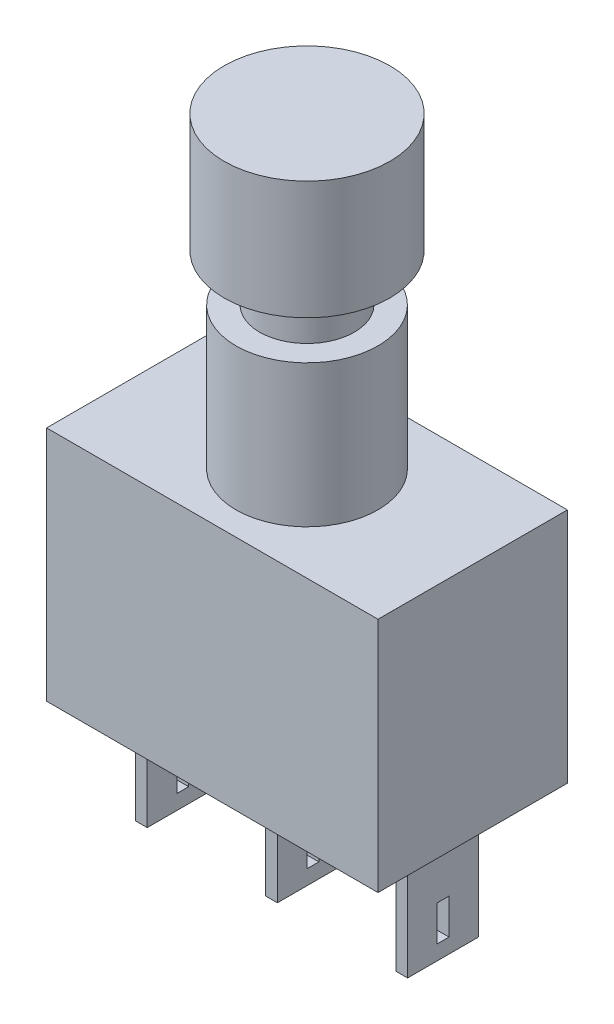
SolidWorks part; units mm, degrees
ref_plane "Front" through (0, 0, 0) normal (0, 0, 1) x (1, 0, 0)
ref_plane "Top" through (0, 0, 0) normal (0, 1, 0) x (1, 0, 0)
ref_plane "Right" through (0, 0, 0) normal (1, 0, 0) x (0, 0, -1)
sketch "Sketch2" plane through (0, 0, 0) normal (0, 1, 0) x (1, 0, 0)
  line L1 (-7, 4) -> (7, 4)
  line L2 (-7, 4) -> (-7, -4)
  line L3 (-7, -4) -> (7, -4)
  line L4 (7, 4) -> (7, -4)
  dimension "D1" = 14
  dimension "D2" = 8
  dimension "D3" = 4
  dimension "D4" = 7
extrude "Extrude1" add sketch "Sketch2" along normal blind 10
sketch "Sketch3" plane through (0, 10, 0) normal (0, 1, 0) x (-1, 0, 0)
  circle A0 centre (0, 0) radius 3
  dimension "D1" = 6
extrude "Extrude2" add sketch "Sketch3" along normal blind 6
sketch "Sketch4" plane through (0, 16, 0) normal (0, 1, 0) x (-1, 0, 0)
  circle A0 centre (0, 0) radius 2
  dimension "D1" = 4
extrude "Extrude3" add sketch "Sketch4" along normal blind 2
sketch "Sketch5" plane through (0, 18, 0) normal (0, 1, 0) x (-1, 0, 0)
  circle A0 centre (0, 0) radius 3.5
  dimension "D1" = 7
extrude "Extrude4" add sketch "Sketch5" along normal blind 5
sketch "Sketch6" plane through (0, 0, 0) normal (0, -1, 0) x (1, 0, 0)
  line L1 (0.25, 1.5) -> (-0.25, 1.5)
  line L2 (0.25, 1.5) -> (0.25, -1.5)
  line L3 (0.25, -1.5) -> (-0.25, -1.5)
  line L4 (-0.25, 1.5) -> (-0.25, -1.5)
  dimension "D1" = 3
  dimension "D2" = 0.5
  dimension "D3" = 1.5
  dimension "D4" = 0.25
extrude "Extrude5" add sketch "Sketch6" along normal blind 5
sketch "Sketch7" plane through (0, 0, 0) normal (0, -1, 0) x (1, 0, 0)
  line L0 (0.25, -1.5) -> (0.25, 1.5) construction
  line L1 (5.75, 1.5) -> (5.25, 1.5)
  line L2 (5.75, 1.5) -> (5.75, -1.5)
  line L3 (5.75, -1.5) -> (5.25, -1.5)
  line L4 (5.25, 1.5) -> (5.25, -1.5)
  line L7 (-7, 4) -> (7, 4) construction
  dimension "D1" = 3
  dimension "D2" = 0.5
  dimension "D3" = 5
  dimension "D4" = 2.5
extrude "Extrude6" add sketch "Sketch7" along normal blind 5
sketch "Sketch8" plane through (0, 0, 0) normal (0, -1, 0) x (1, 0, 0)
  line L0 (-0.25, 1.5) -> (-0.25, -1.5) construction
  line L1 (-5.25, 1.5) -> (-5.75, 1.5)
  line L2 (-5.25, 1.5) -> (-5.25, -1.5)
  line L3 (-5.25, -1.5) -> (-5.75, -1.5)
  line L4 (-5.75, 1.5) -> (-5.75, -1.5)
  line L5 (-7, 4) -> (7, 4) construction
  dimension "D1" = 3
  dimension "D2" = 0.5
  dimension "D3" = 5
  dimension "D4" = 2.5
extrude "Extrude7" add sketch "Sketch8" along normal blind 5
sketch "Sketch9" plane through (-5.75, 0, 0) normal (-1, 0, 0) x (0, 0, 1)
  line L0 (-1.5, -5) -> (-1.5, 0) construction
  line L1 (-0.25, -2.8767) -> (0.25, -2.8767)
  line L2 (-0.25, -2.8767) -> (-0.25, -4.3767)
  line L3 (-0.25, -4.3767) -> (0.25, -4.3767)
  line L4 (0.25, -2.8767) -> (0.25, -4.3767)
  dimension "D1" = 1.5
  dimension "D2" = 0.5
  dimension "D3" = 1.25
extrude "Cut-Extrude1" cut sketch "Sketch9" against normal through all
sketch "Sketch10" plane through (-7, 0, 0) normal (-1, 0, 0) x (0, 0, 1)
  line L0 (0, 29.892) -> (0, -5.892) construction
  line L1 (-8.5556, 23) -> (9.3025, 23) construction
  line L3 (-11.8469, 0) -> (13.8087, 0) construction
  line L4 (-4, 0) -> (4, 0) construction
  line L5 (-9.56, 18) -> (13.8087, 18) construction
  line L6 (-3.5, 18) -> (3.5, 18) construction
  line L9 (3.5, 23) -> (-3.5, 23) construction
  line L10 (-9.56, 16) -> (15.0593, 16) construction
  line L11 (3, 16) -> (-3, 16) construction
  dimension "D1" = 23
